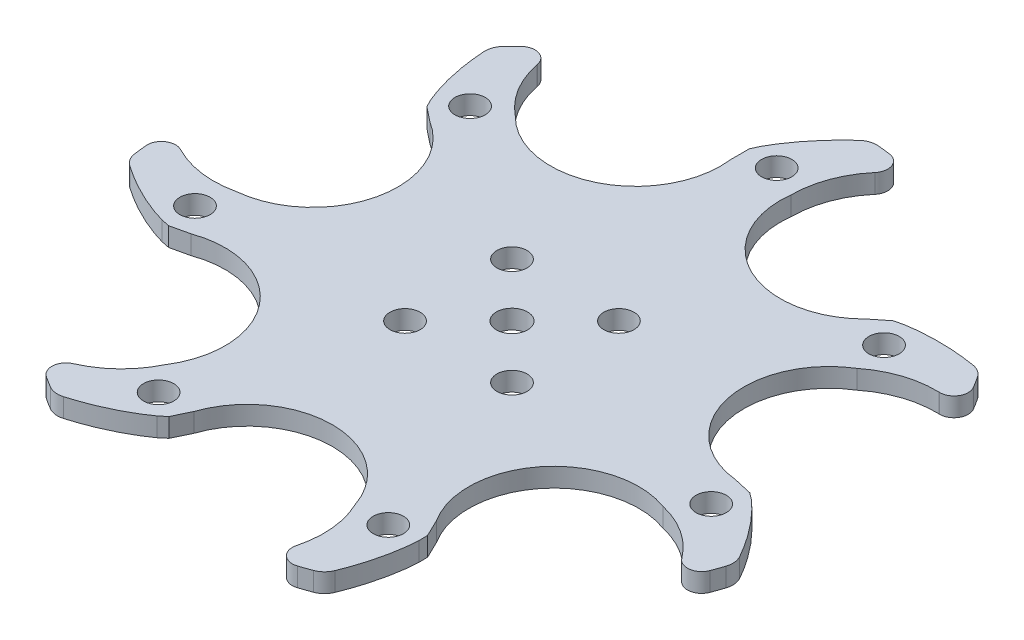
SolidWorks part; units mm, degrees
material "环氧树脂,未充填"
ref_plane "前视基准面" through (0, 0, 0) normal (0, 0, 1) x (1, 0, 0)
ref_plane "上视基准面" through (0, 0, 0) normal (0, 1, 0) x (1, 0, 0)
ref_plane "右视基准面" through (0, 0, 0) normal (1, 0, 0) x (0, 0, -1)
sketch "草图1" plane through (0, 0, 0) normal (0, 1, 0) x (1, 0, 0)
  line L0 (0, 0) -> (-8.5224, -25.1071)
  line L1 (0, 0) -> (8.5224, -25.1071)
  line L2 (0, 0) -> (0, -28)
  line L3 (0, 0) -> (-24.9432, -8.991)
  line L4 (0, 0) -> (-14.3159, -22.3171)
  line L5 (0, 0) -> (-22.5812, 13.8956)
  line L6 (0, 0) -> (-26.3741, -2.7219)
  line L7 (0, 0) -> (-3.2152, 26.3185)
  line L8 (0, 0) -> (-18.572, 18.923)
  line L9 (0, 0) -> (18.572, 18.923)
  line L10 (0, 0) -> (3.2152, 26.3185)
  line L11 (0, 0) -> (26.3741, -2.7219)
  line L12 (0, 0) -> (22.5812, 13.8956)
  line L13 (0, 0) -> (14.3159, -22.3171)
  line L14 (0, 0) -> (24.9432, -8.991)
  line L15 (0, 0) -> (-8.5224, -25.1071) construction
  line L16 (-31.2487, -3.8345) -> (-26.3741, -2.7219)
  line L17 (-14.3159, -22.3171) -> (-8.5224, -25.1071)
  line L18 (-10.6918, -29.612) -> (-16.4853, -26.822)
  line L19 (-16.4853, -26.822) -> (-14.3159, -22.3171)
  line L20 (-10.6918, -29.612) -> (-8.5224, -25.1071)
  line L21 (-29.8178, -10.1036) -> (-24.9432, -8.991)
  line L22 (-22.4812, 22.0405) -> (-18.572, 18.923)
  line L23 (-26.4904, 17.013) -> (-22.5812, 13.8956)
  line L24 (3.2152, 31.3185) -> (3.2152, 26.3185)
  line L25 (-3.2152, 31.3185) -> (-3.2152, 26.3185)
  line L26 (26.4904, 17.013) -> (22.5812, 13.8956)
  line L27 (22.4812, 22.0405) -> (18.572, 18.923)
  line L28 (29.8178, -10.1036) -> (24.9432, -8.991)
  line L29 (31.2487, -3.8345) -> (26.3741, -2.7219)
  line L30 (10.6918, -29.612) -> (8.5224, -25.1071)
  line L31 (16.4853, -26.822) -> (14.3159, -22.3171)
  line L32 (0, 0) -> (-14.3159, -22.3171) construction
  circle A0 centre (0, 0) radius 37
  circle A1 centre (0, -28) radius 9
  circle A2 centre (-21.8913, -17.4577) radius 9
  circle A3 centre (-27.298, 6.2306) radius 9
  circle A4 centre (-12.1487, 25.2271) radius 9
  circle A5 centre (12.1487, 25.2271) radius 9
  circle A6 centre (27.298, 6.2306) radius 9
  circle A7 centre (21.8913, -17.4577) radius 9
  circle A15 centre (-13.5886, -28.217) radius 3.2152
  circle A17 centre (-30.5333, -6.969) radius 3.2152
  circle A18 centre (-24.4858, 19.5268) radius 3.2152
  circle A19 centre (0, 31.3185) radius 3.2152
  circle A20 centre (24.4858, 19.5268) radius 3.2152
  circle A21 centre (30.5333, -6.969) radius 3.2152
  circle A22 centre (13.5886, -28.217) radius 3.2152
  dimension "D1" = 74
  dimension "D2" = 18
  dimension "D4" = 5
  dimension "D3" = 7
  dimension "D5" = 7
extrude "凸台-拉伸1" add sketch "草图1" along normal blind 2 contours A17 L21 L3 L6 L16 | A17 | A2 L4 L3 | L4 L17 L0 | A15 L20 L17 L19 | L18 A15 | A1 L1 L2 | A1 L2 L0 | A22 L31 L13 L1 L30 | A7 L14 L13 | A21 L29 L11 L14 L28 | A6 L12 L11 | A20 L27 L9 L12 L26 | A5 L10 L9 | A19 L25 L7 L10 L24 | A4 L8 L7 | A3 L6 L5 | A18 L23 L5 L8 L22
sketch "草图2" plane through (0, 2, 0) normal (0, 1, 0) x (1, 0, 0)
  line L1 (-5.655, -5.655) -> (5.655, -5.655)
  line L2 (-5.655, -5.655) -> (-5.655, 5.655)
  line L3 (-5.655, 5.655) -> (5.655, 5.655)
  line L4 (5.655, -5.655) -> (5.655, 5.655)
  line L5 (-5.655, -5.655) -> (5.655, 5.655) construction
  line L6 (-5.655, 5.655) -> (5.655, -5.655) construction
  point P0 (0, 0)
  dimension "D1" = 11.31
  dimension "D2" = 11.31
hole_wizard "大小mm Press 暗销孔2" positions "草图3" profile "草图4" hole size "Ø3.0" standard "GB" end condition through all
sketch "草图3" plane through (0, 2, 0) normal (0, 1, 0) x (1, 0, 0)
  point P0 (5.655, -5.655)
  point P3 (5.655, 5.655)
  point P6 (-5.655, 5.655)
  point P9 (-5.655, -5.655)
sketch "草图4" plane through (5.655, 2, 5.655) normal (1, 0, 0) x (0, 0, 1)
  line L0 (0, 0) -> (0, 2)
  line L1 (0, 2) -> (1.6, 2)
  line L2 (1.6, 2) -> (1.6, 0)
  line L5 (1.6, 0) -> (0, 0)
  line L11 (0, -6.35) -> (0, 107.95) construction
  dimension "通孔孔直径" = 3.2
  dimension "通孔孔深度" = 2
sketch "草图5" plane through (0, 2, 0) normal (0, 1, 0) x (1, 0, 0)
  line L0 (0, 0) -> (0, 28)
  line L1 (0, 0) -> (21.8913, 17.4577)
  line L2 (0, 0) -> (27.298, -6.2306)
  line L3 (0, 0) -> (12.1487, -25.2271)
  line L4 (0, 0) -> (-12.1487, -25.2271)
  line L5 (0, 0) -> (-27.298, -6.2306)
  line L6 (0, 0) -> (-21.8913, 17.4577)
  line L7 (0, 0) -> (0, 28) construction
  circle A0 centre (0, 0) radius 28
  dimension "D1" = 56
  dimension "D2" = 7
hole_wizard "大小mm Press 暗销孔2" positions "草图6" profile "草图7" hole size "Ø3.0" standard "GB" end condition through all
sketch "草图6" plane through (0, 2, 0) normal (0, 1, 0) x (1, 0, 0)
  point P0 (-27.298, -6.2306)
  point P3 (-21.8913, 17.4577)
  point P6 (0, 28)
  point P9 (21.8913, 17.4577)
  point P12 (27.298, -6.2306)
  point P15 (12.1487, -25.2271)
  point P18 (-12.1487, -25.2271)
sketch "草图7" plane through (-27.298, 2, 6.2306) normal (1, 0, 0) x (0, 0, 1)
  line L0 (0, 0) -> (0, 2)
  line L1 (0, 2) -> (1.6, 2)
  line L2 (1.6, 2) -> (1.6, 0)
  line L5 (1.6, 0) -> (0, 0)
  line L11 (0, -6.35) -> (0, 107.95) construction
  dimension "通孔孔直径" = 3.2
  dimension "通孔孔深度" = 2
sketch "草图8" plane through (0, 2, 0) normal (0, 1, 0) x (1, 0, 0)
  circle A0 centre (0, 0) radius 1.65
  dimension "D1" = 3.3
extrude "切除-拉伸1" cut sketch "草图8" against normal through all
sketch "草图9" plane through (0, 0, 0) normal (0, -1, 0) x (1, 0, 0)
  line L0 (-22.146, -24.8358) -> (-22.1413, -24.8118)
  line L1 (-3.2152, -28.3069) -> (-3.2152, -26.3185)
  line L2 (-2.8411, -29.1304) -> (-3.2152, -28.3069)
  line L3 (5.6096, -32.7993) -> (5.5938, -32.7807)
  line L4 (20.1266, -20.1627) -> (18.572, -18.923)
  line L5 (21.0036, -20.3837) -> (20.1266, -20.1627)
  line L6 (29.141, -16.0643) -> (29.1167, -16.065)
  line L7 (28.3126, 3.1643) -> (26.3741, 2.7219)
  line L8 (29.0322, 3.7123) -> (28.3126, 3.1643)
  line L9 (30.7287, 12.7675) -> (30.7141, 12.7479)
  line L10 (15.1786, 24.1086) -> (14.3159, 22.3171)
  line L11 (15.1989, 25.0128) -> (15.1786, 24.1086)
  line L12 (9.177, 31.9851) -> (9.1832, 31.9614)
  line L13 (-9.3851, 26.8986) -> (-8.5224, 25.1071)
  line L14 (-10.0795, 27.4782) -> (-9.3851, 26.8986)
  line L15 (-19.2852, 27.1172) -> (-19.2628, 27.1073)
  line L16 (-26.8817, 9.4334) -> (-24.9432, 8.991)
  line L17 (-27.7678, 9.252) -> (-26.8817, 9.4334)
  line L18 (-33.2252, 1.8296) -> (-33.2036, 1.8408)
  line L19 (-24.1358, -15.1353) -> (-22.5812, -13.8956)
  line L20 (-24.5464, -15.9412) -> (-24.1358, -15.1353)
  line L35 (-16.4853, 26.822) -> (-14.3159, 22.3171)
  line L36 (-24.9432, 8.991) -> (-29.8178, 10.1036)
  line L37 (-31.2487, 3.8345) -> (-26.3741, 2.7219)
  line L38 (-22.5812, -13.8956) -> (-26.4904, -17.013)
  line L39 (-22.4812, -22.0405) -> (-18.572, -18.923)
  line L40 (-3.2152, -26.3185) -> (-3.2152, -31.3185)
  line L41 (3.2152, -31.3185) -> (3.2152, -26.3185)
  line L42 (18.572, -18.923) -> (22.4812, -22.0405)
  line L43 (26.4904, -17.013) -> (22.5812, -13.8956)
  line L44 (26.3741, 2.7219) -> (31.2487, 3.8345)
  line L45 (29.8178, 10.1036) -> (24.9432, 8.991)
  line L46 (14.3159, 22.3171) -> (16.4853, 26.822)
  line L47 (10.6918, 29.612) -> (8.5224, 25.1071)
  line L48 (-8.5224, 25.1071) -> (-10.6918, 29.612)
  line L49 (-16.4853, 26.822) -> (-14.3159, 22.3171)
  line L50 (-24.9432, 8.991) -> (-29.8178, 10.1036)
  line L51 (-31.2487, 3.8345) -> (-26.3741, 2.7219)
  line L52 (-22.5812, -13.8956) -> (-26.4904, -17.013)
  line L53 (-22.4812, -22.0405) -> (-18.572, -18.923)
  line L54 (-3.2152, -26.3185) -> (-3.2152, -31.3185)
  line L55 (3.2152, -31.3185) -> (3.2152, -26.3185)
  line L56 (18.572, -18.923) -> (22.4812, -22.0405)
  line L57 (26.4904, -17.013) -> (22.5812, -13.8956)
  line L58 (26.3741, 2.7219) -> (31.2487, 3.8345)
  line L59 (29.8178, 10.1036) -> (24.9432, 8.991)
  line L60 (14.3159, 22.3171) -> (16.4853, 26.822)
  line L61 (10.6918, 29.612) -> (8.5224, 25.1071)
  line L62 (-8.5224, 25.1071) -> (-10.6918, 29.612)
  arc A1 (-26.1541, -23.1777) -> (-25.5975, -24.6919) centre (-24.1581, -23.3034) ccw
  arc A2 (-25.5975, -24.6919) -> (-24.6583, -25.63) centre (0, 0) ccw
  arc A3 (-24.6583, -25.63) -> (-22.146, -24.8358) centre (-23.6183, -24.549) ccw
  arc A4 (-18.572, -18.923) -> (-22.1413, -24.8118) centre (-12.3278, -26.7339) ccw
  arc A5 (-3.2152, -26.3185) -> (-18.572, -18.923) centre (-12.1487, -25.2271) ccw
  arc A6 (1.8142, -34.8992) -> (3.3451, -35.4081) centre (3.157, -33.417) ccw
  arc A7 (3.3451, -35.4081) -> (4.6641, -35.2586) centre (0, 0) ccw
  arc A8 (4.6641, -35.2586) -> (5.6096, -32.7993) centre (4.4674, -33.7716) ccw
  arc A9 (3.2152, -26.3185) -> (5.5938, -32.7807) centre (13.2152, -26.3065) ccw
  arc A10 (18.572, -18.923) -> (3.2152, -26.3185) centre (12.1487, -25.2271) ccw
  arc A11 (28.4164, -20.3409) -> (29.7688, -19.4613) centre (28.0948, -18.3669) ccw
  arc A12 (29.7688, -19.4613) -> (30.4743, -18.3369) centre (0, 0) ccw
  arc A13 (30.4743, -18.3369) -> (29.141, -16.0643) centre (29.1891, -17.5635) ccw
  arc A14 (22.5812, -13.8956) -> (29.1167, -16.065) centre (28.8068, -6.0698) ccw
  arc A15 (26.3741, 2.7219) -> (22.5812, -13.8956) centre (27.298, -6.2306) ccw
  arc A16 (33.6205, 9.5345) -> (33.776, 11.1403) centre (31.8767, 10.5138) ccw
  arc A17 (33.776, 11.1403) -> (33.3368, 12.393) centre (0, 0) ccw
  arc A18 (33.3368, 12.393) -> (30.7287, 12.7675) centre (31.9308, 11.8703) ccw
  arc A19 (24.9432, 8.991) -> (30.7141, 12.7479) centre (22.7063, 18.7376) ccw
  arc A20 (14.3159, 22.3171) -> (24.9432, 8.991) centre (21.8913, 17.4577) ccw
  arc A21 (13.5076, 32.2303) -> (12.3492, 33.353) centre (11.6547, 31.4775) ccw
  arc A22 (12.3492, 33.353) -> (11.0959, 33.7906) centre (0, 0) ccw
  arc A23 (11.0959, 33.7906) -> (9.177, 31.9851) centre (10.628, 32.3655) ccw
  arc A24 (8.5224, 25.1071) -> (9.1832, 31.9614) centre (-0.4925, 29.4352) ccw
  arc A25 (-8.5224, 25.1071) -> (8.5224, 25.1071) centre (0, 28) ccw
  arc A26 (-16.7768, 30.6559) -> (-18.3769, 30.4502) centre (-17.3435, 28.7379) ccw
  arc A27 (-18.3769, 30.4502) -> (-19.5004, 29.7433) centre (0, 0) ccw
  arc A28 (-19.5004, 29.7433) -> (-19.2852, 27.1172) centre (-18.6779, 28.4888) ccw
  arc A29 (-14.3159, 22.3171) -> (-19.2628, 27.1073) centre (-23.3204, 17.9675) ccw
  arc A30 (-24.9432, 8.991) -> (-14.3159, 22.3171) centre (-21.8913, 17.4577) ccw
  arc A31 (-34.4279, 5.9971) -> (-35.2647, 4.6178) centre (-33.2817, 4.3581) ccw
  arc A32 (-35.2647, 4.6178) -> (-35.4125, 3.2986) centre (0, 0) ccw
  arc A33 (-35.4125, 3.2986) -> (-33.2252, 1.8296) centre (-33.919, 3.1595) ccw
  arc A34 (-26.3741, 2.7219) -> (-33.2036, 1.8408) centre (-28.5876, -7.0301) ccw
  arc A35 (-22.5812, -13.8956) -> (-26.3741, 2.7219) centre (-27.298, -6.2306) ccw
  arc A49 (-10.6918, 29.612) -> (-16.4853, 26.822) centre (-13.5886, 28.217) ccw
  arc A50 (-24.9432, 8.991) -> (-14.3159, 22.3171) centre (-21.8913, 17.4577) ccw
  arc A51 (-29.8178, 10.1036) -> (-31.2487, 3.8345) centre (-30.5333, 6.969) ccw
  arc A52 (-22.5812, -13.8956) -> (-26.3741, 2.7219) centre (-27.298, -6.2306) ccw
  arc A53 (-26.4904, -17.013) -> (-22.4812, -22.0405) centre (-24.4858, -19.5268) ccw
  arc A54 (-3.2152, -26.3185) -> (-18.572, -18.923) centre (-12.1487, -25.2271) ccw
  arc A55 (-3.2152, -31.3185) -> (3.2152, -31.3185) centre (0, -31.3185) ccw
  arc A56 (18.572, -18.923) -> (3.2152, -26.3185) centre (12.1487, -25.2271) ccw
  arc A57 (22.4812, -22.0405) -> (26.4904, -17.013) centre (24.4858, -19.5268) ccw
  arc A58 (26.3741, 2.7219) -> (22.5812, -13.8956) centre (27.298, -6.2306) ccw
  arc A59 (31.2487, 3.8345) -> (29.8178, 10.1036) centre (30.5333, 6.969) ccw
  arc A60 (14.3159, 22.3171) -> (24.9432, 8.991) centre (21.8913, 17.4577) ccw
  arc A61 (16.4853, 26.822) -> (10.6918, 29.612) centre (13.5886, 28.217) ccw
  arc A62 (-8.5224, 25.1071) -> (8.5224, 25.1071) centre (0, 28) ccw
  arc A63 (-10.6918, 29.612) -> (-16.4853, 26.822) centre (-13.5886, 28.217) ccw
  arc A64 (-24.9432, 8.991) -> (-14.3159, 22.3171) centre (-21.8913, 17.4577) ccw
  arc A65 (-29.8178, 10.1036) -> (-31.2487, 3.8345) centre (-30.5333, 6.969) ccw
  arc A66 (-22.5812, -13.8956) -> (-26.3741, 2.7219) centre (-27.298, -6.2306) ccw
  arc A67 (-26.4904, -17.013) -> (-22.4812, -22.0405) centre (-24.4858, -19.5268) ccw
  arc A68 (-3.2152, -26.3185) -> (-18.572, -18.923) centre (-12.1487, -25.2271) ccw
  arc A69 (-3.2152, -31.3185) -> (3.2152, -31.3185) centre (0, -31.3185) ccw
  arc A70 (18.572, -18.923) -> (3.2152, -26.3185) centre (12.1487, -25.2271) ccw
  arc A71 (22.4812, -22.0405) -> (26.4904, -17.013) centre (24.4858, -19.5268) ccw
  arc A72 (26.3741, 2.7219) -> (22.5812, -13.8956) centre (27.298, -6.2306) ccw
  arc A73 (31.2487, 3.8345) -> (29.8178, 10.1036) centre (30.5333, 6.969) ccw
  arc A74 (14.3159, 22.3171) -> (24.9432, 8.991) centre (21.8913, 17.4577) ccw
  arc A75 (16.4853, 26.822) -> (10.6918, 29.612) centre (13.5886, 28.217) ccw
  arc A76 (-8.5224, 25.1071) -> (8.5224, 25.1071) centre (0, 28) ccw
  spline S0 degree 3 poles (-24.5464, -15.9412) (-24.5677, -15.992) (-24.6108, -16.0947) (-24.6742, -16.2517) (-24.7378, -16.4133) (-24.8689, -16.7567) (-25.0388, -17.2383) (-25.2375, -17.8705) (-25.4091, -18.48) (-25.5693, -19.1222) (-25.7159, -19.7948) (-25.862, -20.5771) (-25.9969, -21.473) (-26.0794, -22.2234) (-26.123, -22.7352) (-26.1405, -22.9692) (-26.1503, -23.1169) (-26.1541, -23.1777) knots 0 0 0 0 0.019815 0.040153 0.061004 0.082357 0.172565 0.244952 0.32107 0.400636 0.483373 0.569018 0.687296 0.809725 0.840918 0.872328 0.89426 0.89426 0.89426 0.89426
  spline S1 degree 3 poles (-2.8411, -29.1304) (-2.8147, -29.1786) (-2.7612, -29.2764) (-2.678, -29.4239) (-2.5914, -29.5743) (-2.4046, -29.8909) (-2.134, -30.324) (-1.7636, -30.8735) (-1.3941, -31.3877) (-0.9919, -31.9134) (-0.5574, -32.4473) (-0.0369, -33.0493) (0.5795, -33.7134) (1.1147, -34.2458) (1.4877, -34.5989) (1.6597, -34.7585) (1.7691, -34.8583) (1.8142, -34.8992) knots 0 0 0 0 0.019815 0.040153 0.061004 0.082357 0.172565 0.244952 0.32107 0.400636 0.483373 0.569018 0.687296 0.809725 0.840918 0.872328 0.89426 0.89426 0.89426 0.89426
  spline S2 degree 3 poles (21.0036, -20.3837) (21.0578, -20.3932) (21.1676, -20.4123) (21.3348, -20.4393) (21.5065, -20.4653) (21.8704, -20.5167) (22.3778, -20.5751) (23.0383, -20.6281) (23.6707, -20.6598) (24.3325, -20.6732) (25.0208, -20.6664) (25.816, -20.6347) (26.7195, -20.5669) (27.4694, -20.4804) (27.9781, -20.4089) (28.2101, -20.374) (28.3564, -20.3507) (28.4164, -20.3409) knots 0 0 0 0 0.019815 0.040153 0.061004 0.082357 0.172565 0.244952 0.32107 0.400636 0.483373 0.569018 0.687296 0.809725 0.840918 0.872328 0.89426 0.89426 0.89426 0.89426
  spline S3 degree 3 poles (29.0322, 3.7123) (29.0734, 3.7487) (29.1568, 3.8227) (29.2821, 3.9366) (29.4095, 4.0545) (29.6766, 4.307) (30.0386, 4.6672) (30.4919, 5.1507) (30.911, 5.6253) (31.334, 6.1344) (31.7579, 6.6767) (32.2289, 7.3182) (32.7392, 8.0669) (33.1391, 8.7072) (33.4004, 9.1494) (33.5177, 9.3526) (33.5907, 9.4815) (33.6205, 9.5345) knots 0 0 0 0 0.019815 0.040153 0.061004 0.082357 0.172565 0.244952 0.32107 0.400636 0.483373 0.569018 0.687296 0.809725 0.840918 0.872328 0.89426 0.89426 0.89426 0.89426
  spline S4 degree 3 poles (15.1989, 25.0128) (15.1961, 25.0678) (15.1903, 25.1791) (15.1794, 25.3481) (15.1666, 25.5212) (15.1357, 25.8875) (15.0798, 26.3951) (14.9844, 27.0509) (14.8746, 27.6745) (14.7404, 28.3226) (14.5806, 28.9922) (14.3728, 29.7604) (14.1056, 30.6262) (13.8544, 31.338) (13.6715, 31.818) (13.5858, 32.0365) (13.5306, 32.1738) (13.5076, 32.2303) knots 0 0 0 0 0.019815 0.040153 0.061004 0.082357 0.172565 0.244952 0.32107 0.400636 0.483373 0.569018 0.687296 0.809725 0.840918 0.872328 0.89426 0.89426 0.89426 0.89426
  spline S5 degree 3 poles (-10.0795, 27.4782) (-10.1242, 27.5103) (-10.2148, 27.5751) (-10.3537, 27.672) (-10.4971, 27.7699) (-10.8027, 27.9741) (-11.2344, 28.2469) (-11.8066, 28.5813) (-12.3626, 28.8842) (-12.9531, 29.1834) (-13.5761, 29.4759) (-14.3063, 29.7924) (-15.1498, 30.1233) (-15.863, 30.3707) (-16.3523, 30.5271) (-16.5765, 30.5962) (-16.7184, 30.6387) (-16.7768, 30.6559) knots 0 0 0 0 0.019815 0.040153 0.061004 0.082357 0.172565 0.244952 0.32107 0.400636 0.483373 0.569018 0.687296 0.809725 0.840918 0.872328 0.89426 0.89426 0.89426 0.89426
  spline S6 degree 3 poles (-27.7678, 9.252) (-27.8207, 9.237) (-27.9279, 9.2066) (-28.0903, 9.1583) (-28.2562, 9.1073) (-28.6064, 8.9957) (-29.0889, 8.8282) (-29.707, 8.5893) (-30.2906, 8.3435) (-30.8926, 8.0684) (-31.5098, 7.7637) (-32.2125, 7.3901) (-32.9971, 6.937) (-33.6352, 6.5336) (-34.0625, 6.2486) (-34.2564, 6.1164) (-34.378, 6.032) (-34.4279, 5.9971) knots 0 0 0 0 0.019815 0.040153 0.061004 0.082357 0.172565 0.244952 0.32107 0.400636 0.483373 0.569018 0.687296 0.809725 0.840918 0.872328 0.89426 0.89426 0.89426 0.89426
  line M14 (-16.4853, 26.822) -> (-14.3159, 22.3171)
  line M18 (-31.2487, 3.8345) -> (-26.3741, 2.7219)
  line M22 (-22.4812, -22.0405) -> (-18.572, -18.923)
  line M26 (3.2152, -31.3185) -> (3.2152, -26.3185)
  line M30 (26.4904, -17.013) -> (22.5812, -13.8956)
  line M34 (29.8178, 10.1036) -> (24.9432, 8.991)
  line M38 (10.6918, 29.612) -> (8.5224, 25.1071)
  dimension "D1" = 0
extrude "凸台-拉伸2" add sketch "草图9" against normal up to surface (2 mm away) contours A73 S3 A16 A17 A18 L9 A19 M34 | A75 S4 A21 A22 A23 L12 A24 M38 | A63 S5 A26 A27 A28 L15 A29 M14 | A65 S6 A31 A32 A33 L18 A34 M18 | A67 S0 A1 A2 A3 L0 A4 M22 | A69 S1 A6 A7 A8 L3 A9 M26 | A71 S2 A11 A12 A13 L6 A14 M30 up to face at (0, 2, 1.65)
sketch "草图10" plane through (0, 0, 0) normal (0, -1, 0) x (1, 0, 0)
  line L0 (-22.4812, -22.0405) -> (-18.572, -18.923) construction
  line L1 (-22.5812, -13.8956) -> (-26.4904, -17.013) construction
  line L2 (-24.1358, -15.1353) -> (-22.5812, -13.8956) construction
  line L3 (-24.5464, -15.9412) -> (-24.1358, -15.1353) construction
  line L4 (-22.146, -24.8358) -> (-22.1413, -24.8118) construction
  line L5 (-3.2152, -26.3185) -> (-3.2152, -31.3185) construction
  line L6 (3.2152, -31.3185) -> (3.2152, -26.3185) construction
  line L7 (-3.2152, -28.3069) -> (-3.2152, -26.3185) construction
  line L8 (-2.8411, -29.1304) -> (-3.2152, -28.3069) construction
  line L9 (5.6096, -32.7993) -> (5.5938, -32.7807) construction
  line L10 (29.141, -16.0643) -> (29.1167, -16.065) construction
  line L11 (21.0036, -20.3837) -> (20.1266, -20.1627) construction
  line L12 (20.1266, -20.1627) -> (18.572, -18.923) construction
  line L13 (18.572, -18.923) -> (22.4812, -22.0405) construction
  line L14 (26.4904, -17.013) -> (22.5812, -13.8956) construction
  line L15 (30.7287, 12.7675) -> (30.7141, 12.7479) construction
  line L16 (29.0322, 3.7123) -> (28.3126, 3.1643) construction
  line L17 (28.3126, 3.1643) -> (26.3741, 2.7219) construction
  line L18 (29.8178, 10.1036) -> (24.9432, 8.991) construction
  line L19 (26.3741, 2.7219) -> (31.2487, 3.8345) construction
  line L20 (15.1786, 24.1086) -> (14.3159, 22.3171) construction
  line L21 (15.1989, 25.0128) -> (15.1786, 24.1086) construction
  line L22 (9.177, 31.9851) -> (9.1832, 31.9614) construction
  line L23 (14.3159, 22.3171) -> (16.4853, 26.822) construction
  line L24 (10.6918, 29.612) -> (8.5224, 25.1071) construction
  line L25 (-16.4853, 26.822) -> (-14.3159, 22.3171) construction
  line L26 (-8.5224, 25.1071) -> (-10.6918, 29.612) construction
  line L27 (-9.3851, 26.8986) -> (-8.5224, 25.1071) construction
  line L28 (-10.0795, 27.4782) -> (-9.3851, 26.8986) construction
  line L29 (-19.2852, 27.1172) -> (-19.2628, 27.1073) construction
  line L30 (-24.9432, 8.991) -> (-29.8178, 10.1036) construction
  line L31 (-31.2487, 3.8345) -> (-26.3741, 2.7219) construction
  line L32 (-26.8817, 9.4334) -> (-24.9432, 8.991) construction
  line L33 (-27.7678, 9.252) -> (-26.8817, 9.4334) construction
  line L34 (-33.2252, 1.8296) -> (-33.2036, 1.8408) construction
  line L35 (-22.4812, -22.0405) -> (-18.572, -18.923)
  line L36 (-22.5812, -13.8956) -> (-26.4904, -17.013)
  line L37 (-24.1358, -15.1353) -> (-22.5812, -13.8956)
  line L38 (-24.5464, -15.9412) -> (-24.1358, -15.1353)
  line L39 (-22.146, -24.8358) -> (-22.1413, -24.8118)
  line L40 (-3.2152, -26.3185) -> (-3.2152, -31.3185)
  line L41 (3.2152, -31.3185) -> (3.2152, -26.3185)
  line L42 (-3.2152, -28.3069) -> (-3.2152, -26.3185)
  line L43 (-2.8411, -29.1304) -> (-3.2152, -28.3069)
  line L44 (5.6096, -32.7993) -> (5.5938, -32.7807)
  line L45 (29.141, -16.0643) -> (29.1167, -16.065)
  line L46 (21.0036, -20.3837) -> (20.1266, -20.1627)
  line L47 (20.1266, -20.1627) -> (18.572, -18.923)
  line L48 (18.572, -18.923) -> (22.4812, -22.0405)
  line L49 (26.4904, -17.013) -> (22.5812, -13.8956)
  line L50 (30.7287, 12.7675) -> (30.7141, 12.7479)
  line L51 (29.0322, 3.7123) -> (28.3126, 3.1643)
  line L52 (28.3126, 3.1643) -> (26.3741, 2.7219)
  line L53 (29.8178, 10.1036) -> (24.9432, 8.991)
  line L54 (26.3741, 2.7219) -> (31.2487, 3.8345)
  line L55 (15.1786, 24.1086) -> (14.3159, 22.3171)
  line L56 (15.1989, 25.0128) -> (15.1786, 24.1086)
  line L57 (9.177, 31.9851) -> (9.1832, 31.9614)
  line L58 (14.3159, 22.3171) -> (16.4853, 26.822)
  line L59 (10.6918, 29.612) -> (8.5224, 25.1071)
  line L60 (-16.4853, 26.822) -> (-14.3159, 22.3171)
  line L61 (-8.5224, 25.1071) -> (-10.6918, 29.612)
  line L62 (-9.3851, 26.8986) -> (-8.5224, 25.1071)
  line L63 (-10.0795, 27.4782) -> (-9.3851, 26.8986)
  line L64 (-19.2852, 27.1172) -> (-19.2628, 27.1073)
  line L65 (-24.9432, 8.991) -> (-29.8178, 10.1036)
  line L66 (-31.2487, 3.8345) -> (-26.3741, 2.7219)
  line L67 (-26.8817, 9.4334) -> (-24.9432, 8.991)
  line L68 (-27.7678, 9.252) -> (-26.8817, 9.4334)
  line L69 (-33.2252, 1.8296) -> (-33.2036, 1.8408)
  arc A0 (-26.4904, -17.013) -> (-22.4812, -22.0405) centre (-24.4858, -19.5268) ccw construction
  arc A1 (-26.1541, -23.1777) -> (-25.5975, -24.6919) centre (-24.1581, -23.3034) ccw construction
  arc A2 (-25.5975, -24.6919) -> (-24.6583, -25.63) centre (0, 0) ccw construction
  arc A3 (-24.6583, -25.63) -> (-22.146, -24.8358) centre (-23.6183, -24.549) ccw construction
  arc A4 (-18.572, -18.923) -> (-22.1413, -24.8118) centre (-12.3278, -26.7339) ccw construction
  arc A5 (-3.2152, -26.3185) -> (-18.572, -18.923) centre (-12.1487, -25.2271) ccw construction
  arc A6 (-3.2152, -26.3185) -> (-18.572, -18.923) centre (-12.1487, -25.2271) ccw construction
  arc A7 (-3.2152, -31.3185) -> (3.2152, -31.3185) centre (0, -31.3185) ccw construction
  arc A8 (1.8142, -34.8992) -> (3.3451, -35.4081) centre (3.157, -33.417) ccw construction
  arc A9 (3.3451, -35.4081) -> (4.6641, -35.2586) centre (0, 0) ccw construction
  arc A10 (4.6641, -35.2586) -> (5.6096, -32.7993) centre (4.4674, -33.7716) ccw construction
  arc A11 (3.2152, -26.3185) -> (5.5938, -32.7807) centre (13.2152, -26.3065) ccw construction
  arc A12 (18.572, -18.923) -> (3.2152, -26.3185) centre (12.1487, -25.2271) ccw construction
  arc A13 (18.572, -18.923) -> (3.2152, -26.3185) centre (12.1487, -25.2271) ccw construction
  arc A14 (22.5812, -13.8956) -> (29.1167, -16.065) centre (28.8068, -6.0698) ccw construction
  arc A15 (30.4743, -18.3369) -> (29.141, -16.0643) centre (29.1891, -17.5635) ccw construction
  arc A16 (29.7688, -19.4613) -> (30.4743, -18.3369) centre (0, 0) ccw construction
  arc A17 (28.4164, -20.3409) -> (29.7688, -19.4613) centre (28.0948, -18.3669) ccw construction
  arc A18 (22.4812, -22.0405) -> (26.4904, -17.013) centre (24.4858, -19.5268) ccw construction
  arc A19 (26.3741, 2.7219) -> (22.5812, -13.8956) centre (27.298, -6.2306) ccw construction
  arc A20 (26.3741, 2.7219) -> (22.5812, -13.8956) centre (27.298, -6.2306) ccw construction
  arc A21 (24.9432, 8.991) -> (30.7141, 12.7479) centre (22.7063, 18.7376) ccw construction
  arc A22 (33.3368, 12.393) -> (30.7287, 12.7675) centre (31.9308, 11.8703) ccw construction
  arc A23 (33.776, 11.1403) -> (33.3368, 12.393) centre (0, 0) ccw construction
  arc A24 (33.6205, 9.5345) -> (33.776, 11.1403) centre (31.8767, 10.5138) ccw construction
  arc A25 (31.2487, 3.8345) -> (29.8178, 10.1036) centre (30.5333, 6.969) ccw construction
  arc A26 (14.3159, 22.3171) -> (24.9432, 8.991) centre (21.8913, 17.4577) ccw construction
  arc A27 (14.3159, 22.3171) -> (24.9432, 8.991) centre (21.8913, 17.4577) ccw construction
  arc A28 (13.5076, 32.2303) -> (12.3492, 33.353) centre (11.6547, 31.4775) ccw construction
  arc A29 (12.3492, 33.353) -> (11.0959, 33.7906) centre (0, 0) ccw construction
  arc A30 (11.0959, 33.7906) -> (9.177, 31.9851) centre (10.628, 32.3655) ccw construction
  arc A31 (8.5224, 25.1071) -> (9.1832, 31.9614) centre (-0.4925, 29.4352) ccw construction
  arc A32 (16.4853, 26.822) -> (10.6918, 29.612) centre (13.5886, 28.217) ccw construction
  arc A33 (-8.5224, 25.1071) -> (8.5224, 25.1071) centre (0, 28) ccw construction
  arc A34 (-8.5224, 25.1071) -> (8.5224, 25.1071) centre (0, 28) ccw construction
  arc A35 (-10.6918, 29.612) -> (-16.4853, 26.822) centre (-13.5886, 28.217) ccw construction
  arc A36 (-16.7768, 30.6559) -> (-18.3769, 30.4502) centre (-17.3435, 28.7379) ccw construction
  arc A37 (-18.3769, 30.4502) -> (-19.5004, 29.7433) centre (0, 0) ccw construction
  arc A38 (-19.5004, 29.7433) -> (-19.2852, 27.1172) centre (-18.6779, 28.4888) ccw construction
  arc A39 (-14.3159, 22.3171) -> (-19.2628, 27.1073) centre (-23.3204, 17.9675) ccw construction
  arc A40 (-24.9432, 8.991) -> (-14.3159, 22.3171) centre (-21.8913, 17.4577) ccw construction
  arc A41 (-24.9432, 8.991) -> (-14.3159, 22.3171) centre (-21.8913, 17.4577) ccw construction
  arc A42 (-29.8178, 10.1036) -> (-31.2487, 3.8345) centre (-30.5333, 6.969) ccw construction
  arc A43 (-34.4279, 5.9971) -> (-35.2647, 4.6178) centre (-33.2817, 4.3581) ccw construction
  arc A44 (-35.2647, 4.6178) -> (-35.4125, 3.2986) centre (0, 0) ccw construction
  arc A45 (-35.4125, 3.2986) -> (-33.2252, 1.8296) centre (-33.919, 3.1595) ccw construction
  arc A46 (-26.3741, 2.7219) -> (-33.2036, 1.8408) centre (-28.5876, -7.0301) ccw construction
  arc A47 (-22.5812, -13.8956) -> (-26.3741, 2.7219) centre (-27.298, -6.2306) ccw construction
  arc A48 (-22.5812, -13.8956) -> (-26.3741, 2.7219) centre (-27.298, -6.2306) ccw construction
  arc A49 (-26.4904, -17.013) -> (-22.4812, -22.0405) centre (-24.4858, -19.5268) ccw
  arc A50 (-26.1541, -23.1777) -> (-25.5975, -24.6919) centre (-24.1581, -23.3034) ccw
  arc A51 (-25.5975, -24.6919) -> (-24.6583, -25.63) centre (0, 0) ccw
  arc A52 (-24.6583, -25.63) -> (-22.146, -24.8358) centre (-23.6183, -24.549) ccw
  arc A53 (-18.572, -18.923) -> (-22.1413, -24.8118) centre (-12.3278, -26.7339) ccw
  arc A54 (-3.2152, -26.3185) -> (-18.572, -18.923) centre (-12.1487, -25.2271) ccw
  arc A55 (-3.2152, -26.3185) -> (-18.572, -18.923) centre (-12.1487, -25.2271) ccw
  arc A56 (-3.2152, -31.3185) -> (3.2152, -31.3185) centre (0, -31.3185) ccw
  arc A57 (1.8142, -34.8992) -> (3.3451, -35.4081) centre (3.157, -33.417) ccw
  arc A58 (3.3451, -35.4081) -> (4.6641, -35.2586) centre (0, 0) ccw
  arc A59 (4.6641, -35.2586) -> (5.6096, -32.7993) centre (4.4674, -33.7716) ccw
  arc A60 (3.2152, -26.3185) -> (5.5938, -32.7807) centre (13.2152, -26.3065) ccw
  arc A61 (18.572, -18.923) -> (3.2152, -26.3185) centre (12.1487, -25.2271) ccw
  arc A62 (18.572, -18.923) -> (3.2152, -26.3185) centre (12.1487, -25.2271) ccw
  arc A63 (22.5812, -13.8956) -> (29.1167, -16.065) centre (28.8068, -6.0698) ccw
  arc A64 (30.4743, -18.3369) -> (29.141, -16.0643) centre (29.1891, -17.5635) ccw
  arc A65 (29.7688, -19.4613) -> (30.4743, -18.3369) centre (0, 0) ccw
  arc A66 (28.4164, -20.3409) -> (29.7688, -19.4613) centre (28.0948, -18.3669) ccw
  arc A67 (22.4812, -22.0405) -> (26.4904, -17.013) centre (24.4858, -19.5268) ccw
  arc A68 (26.3741, 2.7219) -> (22.5812, -13.8956) centre (27.298, -6.2306) ccw
  arc A69 (26.3741, 2.7219) -> (22.5812, -13.8956) centre (27.298, -6.2306) ccw
  arc A70 (24.9432, 8.991) -> (30.7141, 12.7479) centre (22.7063, 18.7376) ccw
  arc A71 (33.3368, 12.393) -> (30.7287, 12.7675) centre (31.9308, 11.8703) ccw
  arc A72 (33.776, 11.1403) -> (33.3368, 12.393) centre (0, 0) ccw
  arc A73 (33.6205, 9.5345) -> (33.776, 11.1403) centre (31.8767, 10.5138) ccw
  arc A74 (31.2487, 3.8345) -> (29.8178, 10.1036) centre (30.5333, 6.969) ccw
  arc A75 (14.3159, 22.3171) -> (24.9432, 8.991) centre (21.8913, 17.4577) ccw
  arc A76 (14.3159, 22.3171) -> (24.9432, 8.991) centre (21.8913, 17.4577) ccw
  arc A77 (13.5076, 32.2303) -> (12.3492, 33.353) centre (11.6547, 31.4775) ccw
  arc A78 (12.3492, 33.353) -> (11.0959, 33.7906) centre (0, 0) ccw
  arc A79 (11.0959, 33.7906) -> (9.177, 31.9851) centre (10.628, 32.3655) ccw
  arc A80 (8.5224, 25.1071) -> (9.1832, 31.9614) centre (-0.4925, 29.4352) ccw
  arc A81 (16.4853, 26.822) -> (10.6918, 29.612) centre (13.5886, 28.217) ccw
  arc A82 (-8.5224, 25.1071) -> (8.5224, 25.1071) centre (0, 28) ccw
  arc A83 (-8.5224, 25.1071) -> (8.5224, 25.1071) centre (0, 28) ccw
  arc A84 (-10.6918, 29.612) -> (-16.4853, 26.822) centre (-13.5886, 28.217) ccw
  arc A85 (-16.7768, 30.6559) -> (-18.3769, 30.4502) centre (-17.3435, 28.7379) ccw
  arc A86 (-18.3769, 30.4502) -> (-19.5004, 29.7433) centre (0, 0) ccw
  arc A87 (-19.5004, 29.7433) -> (-19.2852, 27.1172) centre (-18.6779, 28.4888) ccw
  arc A88 (-14.3159, 22.3171) -> (-19.2628, 27.1073) centre (-23.3204, 17.9675) ccw
  arc A89 (-24.9432, 8.991) -> (-14.3159, 22.3171) centre (-21.8913, 17.4577) ccw
  arc A90 (-24.9432, 8.991) -> (-14.3159, 22.3171) centre (-21.8913, 17.4577) ccw
  arc A91 (-29.8178, 10.1036) -> (-31.2487, 3.8345) centre (-30.5333, 6.969) ccw
  arc A92 (-34.4279, 5.9971) -> (-35.2647, 4.6178) centre (-33.2817, 4.3581) ccw
  arc A93 (-35.2647, 4.6178) -> (-35.4125, 3.2986) centre (0, 0) ccw
  arc A94 (-35.4125, 3.2986) -> (-33.2252, 1.8296) centre (-33.919, 3.1595) ccw
  arc A95 (-26.3741, 2.7219) -> (-33.2036, 1.8408) centre (-28.5876, -7.0301) ccw
  arc A96 (-22.5812, -13.8956) -> (-26.3741, 2.7219) centre (-27.298, -6.2306) ccw
  arc A97 (-22.5812, -13.8956) -> (-26.3741, 2.7219) centre (-27.298, -6.2306) ccw
  spline S0 degree 3 poles (-2783.4755, 1161.0692) (-2.3416, -0.7046) (-20.3717, -5.61) (-24.6742, -16.2517) (-24.7378, -16.4133) (-24.8689, -16.7567) (-25.0388, -17.2383) (-25.2375, -17.8705) (-25.4091, -18.48) (-25.5693, -19.1222) (-25.7159, -19.7948) (-25.862, -20.5771) (-25.9969, -21.473) (-26.0794, -22.2234) (-26.123, -22.7352) (-30.4467, -80.4189) (154.458, -151.2894) (2797.8729, 969.9962) knots -4.074078 -4.074078 -4.074078 -4.074078 0.019815 0.040153 0.061004 0.082357 0.172565 0.244952 0.32107 0.400636 0.483373 0.569018 0.687296 0.809725 0.840918 0.872328 21.648297 21.648297 21.648297 21.648297 only from (-24.5464, -15.9412) to (-26.1541, -23.1777) construction
  spline S1 degree 3 poles (-2643.2292, -1452.294) (-0.9091, -2.2701) (-8.3155, -19.425) (-2.678, -29.4239) (-2.5914, -29.5743) (-2.4046, -29.8909) (-2.134, -30.324) (-1.7636, -30.8735) (-1.3941, -31.3877) (-0.9919, -31.9134) (-0.5574, -32.4473) (-0.0369, -33.0493) (0.5795, -33.7134) (1.1147, -34.2458) (1.4877, -34.5989) (43.8908, -73.9445) (214.5858, 26.4327) (986.0717, 2792.2479) knots -4.074078 -4.074078 -4.074078 -4.074078 0.019815 0.040153 0.061004 0.082357 0.172565 0.244952 0.32107 0.400636 0.483373 0.569018 0.687296 0.809725 0.840918 0.872328 21.648297 21.648297 21.648297 21.648297 only from (-2.8411, -29.1304) to (1.8142, -34.8992) construction
  spline S2 degree 3 poles (-512.5771, -2972.0499) (1.208, -2.1261) (10.0025, -18.6126) (21.3348, -20.4393) (21.5065, -20.4653) (21.8704, -20.5167) (22.3778, -20.5751) (23.0383, -20.6281) (23.6707, -20.6598) (24.3325, -20.6732) (25.0208, -20.6664) (25.816, -20.6347) (26.7195, -20.5669) (27.4694, -20.4804) (27.9781, -20.4089) (85.1776, -11.7884) (113.1261, 184.2504) (-1568.2617, 2511.88) knots -4.074078 -4.074078 -4.074078 -4.074078 0.019815 0.040153 0.061004 0.082357 0.172565 0.244952 0.32107 0.400636 0.483373 0.569018 0.687296 0.809725 0.840918 0.872328 21.648297 21.648297 21.648297 21.648297 only from (21.0036, -20.3837) to (28.4164, -20.3409) construction
  spline S3 degree 3 poles (2004.056, -2253.792) (2.4155, -0.3812) (20.7883, -3.7845) (29.2821, 3.9366) (29.4095, 4.0545) (29.6766, 4.307) (30.0386, 4.6672) (30.4919, 5.1507) (30.911, 5.6253) (31.334, 6.1344) (31.7579, 6.6767) (32.2289, 7.3182) (32.7392, 8.0669) (33.1391, 8.7072) (33.4004, 9.1494) (62.3239, 59.2446) (-73.5198, 203.3238) (-2941.662, 340.0152) knots -4.074078 -4.074078 -4.074078 -4.074078 0.019815 0.040153 0.061004 0.082357 0.172565 0.244952 0.32107 0.400636 0.483373 0.569018 0.687296 0.809725 0.840918 0.872328 21.648297 21.648297 21.648297 21.648297 only from (29.0322, 3.7123) to (33.6205, 9.5345) construction
  spline S4 degree 3 poles (3011.5935, 161.6175) (1.804, 1.6508) (15.9202, 13.8934) (15.1794, 25.3481) (15.1666, 25.5212) (15.1357, 25.8875) (15.0798, 26.3951) (14.9844, 27.0509) (14.8746, 27.6745) (14.7404, 28.3226) (14.5806, 28.9922) (14.3728, 29.7604) (14.1056, 30.6262) (13.8544, 31.338) (13.6715, 31.818) (-7.4609, 85.6652) (-204.8038, 69.2902) (-2099.9308, -2087.888) knots -4.074078 -4.074078 -4.074078 -4.074078 0.019815 0.040153 0.061004 0.082357 0.172565 0.244952 0.32107 0.400636 0.483373 0.569018 0.687296 0.809725 0.840918 0.872328 21.648297 21.648297 21.648297 21.648297 only from (15.1989, 25.0128) to (13.5076, 32.2303) construction
  spline S5 degree 3 poles (1751.3406, 2455.3257) (-0.1659, 2.4397) (-0.9362, 21.1093) (-10.3537, 27.672) (-10.4971, 27.7699) (-10.8027, 27.9741) (-11.2344, 28.2469) (-11.8066, 28.5813) (-12.3626, 28.8842) (-12.9531, 29.1834) (-13.5761, 29.4759) (-14.3063, 29.7924) (-15.1498, 30.1233) (-15.863, 30.3707) (-16.3523, 30.5271) (-71.6276, 47.5782) (-181.8664, -116.9203) (323.0911, -2943.5689) knots -4.074078 -4.074078 -4.074078 -4.074078 0.019815 0.040153 0.061004 0.082357 0.172565 0.244952 0.32107 0.400636 0.483373 0.569018 0.687296 0.809725 0.840918 0.872328 21.648297 21.648297 21.648297 21.648297 only from (-10.0795, 27.4782) to (-16.7768, 30.6559) construction
  spline S6 degree 3 poles (-827.7084, 2900.124) (-2.0109, 1.3915) (-17.0876, 12.4295) (-28.0903, 9.1583) (-28.2562, 9.1073) (-28.6064, 8.9957) (-29.0889, 8.8282) (-29.707, 8.5893) (-30.2906, 8.3435) (-30.8926, 8.0684) (-31.5098, 7.7637) (-32.2125, 7.3901) (-32.9971, 6.937) (-33.6352, 6.5336) (-34.0625, 6.2486) (-81.8572, -26.3362) (-21.9798, -215.0875) (2502.8188, -1582.6824) knots -4.074078 -4.074078 -4.074078 -4.074078 0.019815 0.040153 0.061004 0.082357 0.172565 0.244952 0.32107 0.400636 0.483373 0.569018 0.687296 0.809725 0.840918 0.872328 21.648297 21.648297 21.648297 21.648297 only from (-27.7678, 9.252) to (-34.4279, 5.9971) construction
  spline S7 degree 3 poles (-24.5464, -15.9412) (-24.5677, -15.992) (-24.6108, -16.0947) (-24.6742, -16.2517) (-24.7378, -16.4133) (-24.8689, -16.7567) (-25.0388, -17.2383) (-25.2375, -17.8705) (-25.4091, -18.48) (-25.5693, -19.1222) (-25.7159, -19.7948) (-25.862, -20.5771) (-25.9969, -21.473) (-26.0794, -22.2234) (-26.123, -22.7352) (-26.1405, -22.9692) (-26.1503, -23.1169) (-26.1541, -23.1777) knots 0 0 0 0 0.019815 0.040153 0.061004 0.082357 0.172565 0.244952 0.32107 0.400636 0.483373 0.569018 0.687296 0.809725 0.840918 0.872328 0.89426 0.89426 0.89426 0.89426
  spline S8 degree 3 poles (-2.8411, -29.1304) (-2.8147, -29.1786) (-2.7612, -29.2764) (-2.678, -29.4239) (-2.5914, -29.5743) (-2.4046, -29.8909) (-2.134, -30.324) (-1.7636, -30.8735) (-1.3941, -31.3877) (-0.9919, -31.9134) (-0.5574, -32.4473) (-0.0369, -33.0493) (0.5795, -33.7134) (1.1147, -34.2458) (1.4877, -34.5989) (1.6597, -34.7585) (1.7691, -34.8583) (1.8142, -34.8992) knots 0 0 0 0 0.019815 0.040153 0.061004 0.082357 0.172565 0.244952 0.32107 0.400636 0.483373 0.569018 0.687296 0.809725 0.840918 0.872328 0.89426 0.89426 0.89426 0.89426
  spline S9 degree 3 poles (21.0036, -20.3837) (21.0578, -20.3932) (21.1676, -20.4123) (21.3348, -20.4393) (21.5065, -20.4653) (21.8704, -20.5167) (22.3778, -20.5751) (23.0383, -20.6281) (23.6707, -20.6598) (24.3325, -20.6732) (25.0208, -20.6664) (25.816, -20.6347) (26.7195, -20.5669) (27.4694, -20.4804) (27.9781, -20.4089) (28.2101, -20.374) (28.3564, -20.3507) (28.4164, -20.3409) knots 0 0 0 0 0.019815 0.040153 0.061004 0.082357 0.172565 0.244952 0.32107 0.400636 0.483373 0.569018 0.687296 0.809725 0.840918 0.872328 0.89426 0.89426 0.89426 0.89426
  spline S10 degree 3 poles (29.0322, 3.7123) (29.0734, 3.7487) (29.1568, 3.8227) (29.2821, 3.9366) (29.4095, 4.0545) (29.6766, 4.307) (30.0386, 4.6672) (30.4919, 5.1507) (30.911, 5.6253) (31.334, 6.1344) (31.7579, 6.6767) (32.2289, 7.3182) (32.7392, 8.0669) (33.1391, 8.7072) (33.4004, 9.1494) (33.5177, 9.3526) (33.5907, 9.4815) (33.6205, 9.5345) knots 0 0 0 0 0.019815 0.040153 0.061004 0.082357 0.172565 0.244952 0.32107 0.400636 0.483373 0.569018 0.687296 0.809725 0.840918 0.872328 0.89426 0.89426 0.89426 0.89426
  spline S11 degree 3 poles (15.1989, 25.0128) (15.1961, 25.0678) (15.1903, 25.1791) (15.1794, 25.3481) (15.1666, 25.5212) (15.1357, 25.8875) (15.0798, 26.3951) (14.9844, 27.0509) (14.8746, 27.6745) (14.7404, 28.3226) (14.5806, 28.9922) (14.3728, 29.7604) (14.1056, 30.6262) (13.8544, 31.338) (13.6715, 31.818) (13.5858, 32.0365) (13.5306, 32.1738) (13.5076, 32.2303) knots 0 0 0 0 0.019815 0.040153 0.061004 0.082357 0.172565 0.244952 0.32107 0.400636 0.483373 0.569018 0.687296 0.809725 0.840918 0.872328 0.89426 0.89426 0.89426 0.89426
  spline S12 degree 3 poles (-10.0795, 27.4782) (-10.1242, 27.5103) (-10.2148, 27.5751) (-10.3537, 27.672) (-10.4971, 27.7699) (-10.8027, 27.9741) (-11.2344, 28.2469) (-11.8066, 28.5813) (-12.3626, 28.8842) (-12.9531, 29.1834) (-13.5761, 29.4759) (-14.3063, 29.7924) (-15.1498, 30.1233) (-15.863, 30.3707) (-16.3523, 30.5271) (-16.5765, 30.5962) (-16.7184, 30.6387) (-16.7768, 30.6559) knots 0 0 0 0 0.019815 0.040153 0.061004 0.082357 0.172565 0.244952 0.32107 0.400636 0.483373 0.569018 0.687296 0.809725 0.840918 0.872328 0.89426 0.89426 0.89426 0.89426
  spline S13 degree 3 poles (-27.7678, 9.252) (-27.8207, 9.237) (-27.9279, 9.2066) (-28.0903, 9.1583) (-28.2562, 9.1073) (-28.6064, 8.9957) (-29.0889, 8.8282) (-29.707, 8.5893) (-30.2906, 8.3435) (-30.8926, 8.0684) (-31.5098, 7.7637) (-32.2125, 7.3901) (-32.9971, 6.937) (-33.6352, 6.5336) (-34.0625, 6.2486) (-34.2564, 6.1164) (-34.378, 6.032) (-34.4279, 5.9971) knots 0 0 0 0 0.019815 0.040153 0.061004 0.082357 0.172565 0.244952 0.32107 0.400636 0.483373 0.569018 0.687296 0.809725 0.840918 0.872328 0.89426 0.89426 0.89426 0.89426
extrude "切除-拉伸2" cut sketch "草图10" against normal blind 10 contours S10 L51 L54 A74 | S9 L46 L48 A67 | S11 L56 L58 A81 | S12 L63 L61 A84 | S13 L68 L65 A91 | S7 L38 L36 A49 | S8 L43 L40 A56
